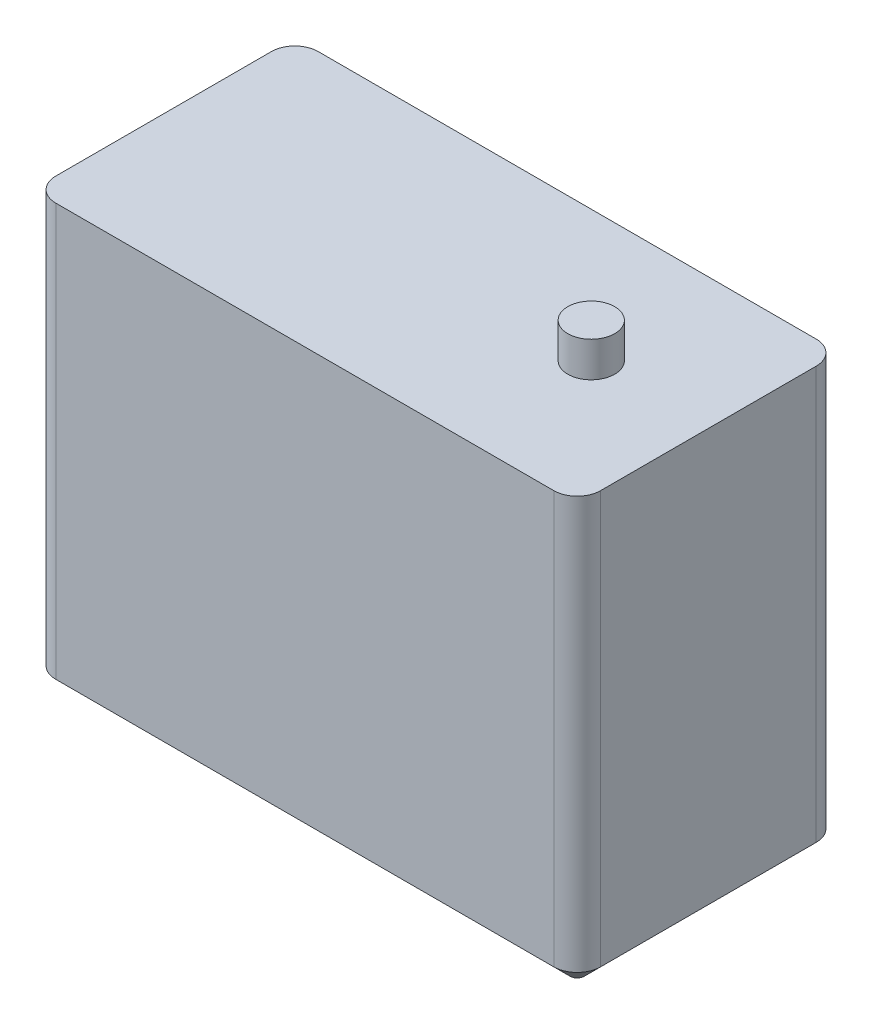
SolidWorks part; units mm, degrees
ref_plane "Front Plane" through (0, 0, 0) normal (0, 0, 1) x (1, 0, 0)
ref_plane "Top Plane" through (0, 0, 0) normal (0, 1, 0) x (1, 0, 0)
ref_plane "Right Plane" through (0, 0, 0) normal (1, 0, 0) x (0, 0, -1)
sketch "Sketch1" plane through (0, 0, 0) normal (0, 1, 0) x (1, 0, 0)
  line L1 (-31.8715, -23.9829) -> (27.1835, -23.9829)
  line L2 (-31.8715, -23.9829) -> (-31.8715, 4.4651)
  line L3 (-31.8715, 4.4651) -> (27.1835, 4.4651)
  line L4 (27.1835, -23.9829) -> (27.1835, 4.4651)
  dimension "D1" = 59.055
  dimension "D2" = 28.448
extrude "Boss-Extrude1" add sketch "Sketch1" along normal blind 46.482
sketch "Sketch2" plane through (0, 46.482, 0) normal (0, 1, 0) x (1, 0, 0)
  line L0 (27.1835, -9.7589) -> (14.4835, -9.7589)
  line L1 (27.1835, -23.9829) -> (27.1835, 4.4651) construction
  circle A0 centre (14.4835, -9.7589) radius 2.54
  dimension "D1" = 12.7
extrude "Boss-Extrude2" add sketch "Sketch2" along normal blind 3.81
fillet "Fillet1" radius 2.54 4 edges at (-31.8715, 23.241, -4.4651) (27.1835, 23.241, -4.4651) (27.1835, 23.241, 23.9829) (-31.8715, 23.241, 23.9829)
chamfer "Chamfer1" distance 1.778 angle 45 8 edges at (-31.1276, 0, -3.7211) (-2.344, 0, -4.4651) (26.4395, 0, -3.7211) (-31.8715, 0, 9.7589) (-31.1276, 0, 23.239) (-2.344, 0, 23.9829) (26.4395, 0, 23.239) (27.1835, 0, 9.7589)
